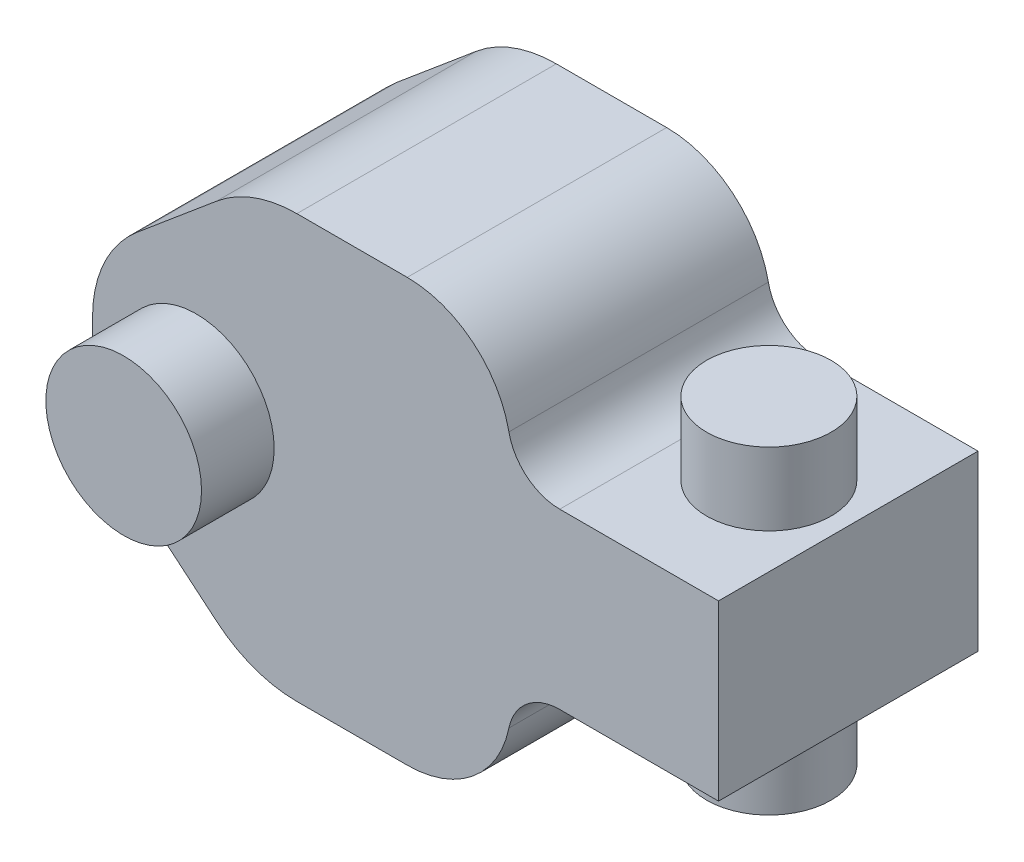
SolidWorks part; units mm, degrees
ref_plane "Alzado" through (0, 0, 0) normal (0, 0, 1) x (1, 0, 0)
ref_plane "Planta" through (0, 0, 0) normal (0, 1, 0) x (1, 0, 0)
ref_plane "Vista lateral" through (0, 0, 0) normal (1, 0, 0) x (0, 0, -1)
sketch "Croquis1" plane through (0, 0, 0) normal (0, 0, 1) x (1, 0, 0)
  line L0 (4.1477, -1.5793) -> (-36.4847, -1.5793)
  line L1 (-44.1981, -4.3867) -> (-51.8867, -10.8382)
  line L2 (-56.1732, -20.0307) -> (-56.1732, -23.8393)
  line L3 (-51.8867, -33.0319) -> (-44.1981, -39.4833)
  line L4 (-36.4847, -42.2908) -> (4.1477, -42.2908)
  line L5 (4.1477, -42.2908) -> (4.1477, -1.5793)
  arc A0 (-44.1981, -39.4833) -> (-36.4847, -42.2908) centre (-36.4847, -30.2908) ccw
  arc A1 (-56.1732, -23.8393) -> (-51.8867, -33.0319) centre (-44.1732, -23.8393) ccw
  arc A2 (-51.8867, -10.8382) -> (-56.1732, -20.0307) centre (-44.1732, -20.0307) ccw
  arc A3 (-36.4847, -1.5793) -> (-44.1981, -4.3867) centre (-36.4847, -13.5793) ccw
  point P8 (-40.8523, -42.2908)
  point P11 (-56.1732, -29.435)
  point P14 (-56.1732, -14.435)
  point P17 (-40.8523, -1.5793)
  dimension "D7" = 12
  dimension "D1" = 140
  dimension "D2" = 140
  dimension "D3" = 15
  dimension "D4" = 20
  dimension "D5" = 20
  dimension "D6" = 45
  dimension "D8" = 40.7115
extrude "Saliente-Extruir1" add sketch "Croquis1" along normal mid plane 25
sketch "Croquis3" plane through (0, 0, 0) normal (0, 0, 1) x (1, 0, 0)
  line L0 (-56.1732, -20.0307) -> (-56.1732, -23.8393) construction
  line L1 (-36.4847, -42.2908) -> (4.1477, -42.2908) construction
  line L2 (4.1477, -1.5793) -> (-36.4847, -1.5793) construction
  circle A0 centre (-46.1732, -22.2908) radius 7.5
  dimension "D1" = 15
  dimension "D2" = 10
  dimension "D3" = 20
  dimension "D4" = 20.7115
extrude "Saliente-Extruir2" add sketch "Croquis3" along normal mid plane 39
sketch "Croquis4" plane through (0, -1.5793, 0) normal (0, 1, 0) x (1, 0, 0)
  line L0 (4.1477, 12.5) -> (-36.4847, 12.5) construction
  line L1 (-15.8523, 12.5) -> (4.1477, 12.5)
  line L2 (-15.8523, 12.5) -> (-15.8523, -12.5)
  line L3 (-15.8523, -12.5) -> (4.1477, -12.5)
  line L4 (4.1477, 12.5) -> (4.1477, -12.5)
  dimension "D1" = 20
extrude "Cortar-Extruir1" cut sketch "Croquis4" against normal blind 12
sketch "Croquis5" plane through (0, -42.2908, 0) normal (0, -1, 0) x (1, 0, 0)
  line L0 (-36.4847, -12.5) -> (4.1477, -12.5) construction
  line L1 (4.1477, 12.5) -> (-15.8523, 12.5)
  line L2 (4.1477, 12.5) -> (4.1477, -12.5)
  line L3 (4.1477, -12.5) -> (-15.8523, -12.5)
  line L4 (-15.8523, 12.5) -> (-15.8523, -12.5)
  dimension "D1" = 20
extrude "Cortar-Extruir2" cut sketch "Croquis5" against normal blind 12
fillet "Redondeo1" radius 10 2 edges at (-15.8523, -1.5793, 0) (-15.8523, -42.2908, 0)
fillet "Redondeo2" radius 5 2 edges at (-15.8523, -13.5793, 0) (-15.8523, -30.2908, 0)
sketch "Croquis7" plane through (0, -13.5793, 0) normal (0, 1, 0) x (1, 0, 0)
  line L0 (4.1477, 12.5) -> (-11.1554, 12.5) construction
  line L3 (4.1477, -12.5) -> (4.1477, 12.5) construction
  circle A0 centre (-3.5023, 0) radius 6
  point P4 (-3.5039, 12.5)
  dimension "D1" = 12.5
  dimension "D2" = 7.65
  dimension "D3" = 12
extrude "Saliente-Extruir4" add sketch "Croquis7" along normal blind 7
sketch "Croquis8" plane through (0, -30.2908, 0) normal (0, -1, 0) x (1, 0, 0)
  line L0 (4.1477, 12.5) -> (-11.1554, 12.5) construction
  line L1 (4.1477, -12.5) -> (4.1477, 12.5) construction
  circle A0 centre (-3.5023, 0) radius 6
  dimension "D1" = 12
  dimension "D2" = 12.5
  dimension "D3" = 7.65
extrude "Saliente-Extruir5" add sketch "Croquis8" along normal blind 7
